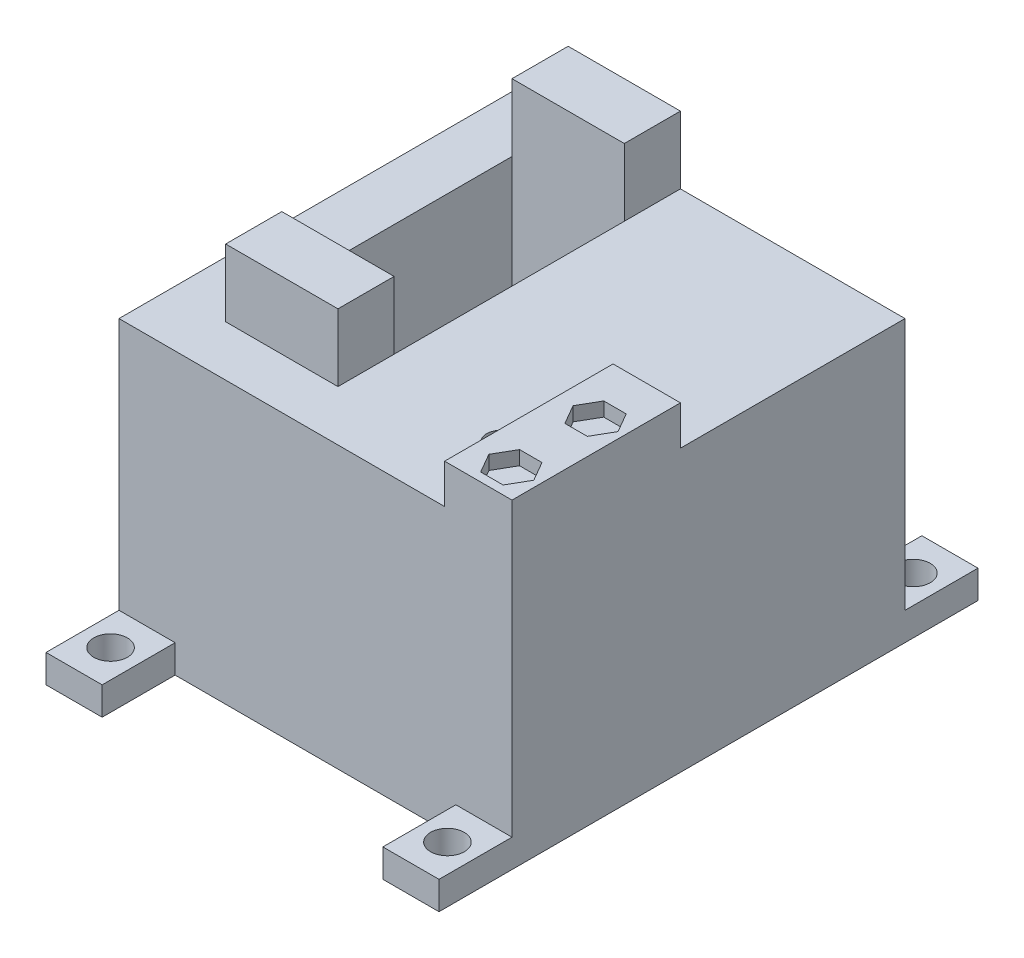
SolidWorks part; units mm, degrees
ref_plane "Front Plane" through (0, 0, 0) normal (0, 0, 1) x (1, 0, 0)
ref_plane "Top Plane" through (0, 0, 0) normal (0, 1, 0) x (1, 0, 0)
ref_plane "Right Plane" through (0, 0, 0) normal (1, 0, 0) x (0, 0, -1)
sketch "Sketch1" plane through (0, 0, 0) normal (0, 1, 0) x (1, 0, 0)
  line L1 (35, 35) -> (-35, 35)
  line L2 (35, 35) -> (35, -35)
  line L3 (35, -35) -> (-35, -35)
  line L4 (-35, 35) -> (-35, -35)
  line L5 (35, 35) -> (-35, -35) construction
  line L6 (35, -35) -> (-35, 35) construction
  point P0 (0, 0)
extrude "Boss-Extrude1" add sketch "Sketch1" along normal blind 50
sketch "Sketch2" plane through (0, 0, 0) normal (0, -1, 0) x (1, 0, 0)
  line L1 (0, 25) -> (-25, 25)
  line L2 (-25, 25) -> (-25, -25)
  line L3 (-25, -25) -> (25, -25)
  line L4 (0, 25) -> (25, 25)
  line L5 (25, 25) -> (25, -25)
extrude "Cut-Extrude1" cut sketch "Sketch2" against normal blind 40
sketch "Sketch3" plane through (0, 50, 0) normal (0, 1, 0) x (1, 0, 0)
  line L11 (-25, 25) -> (-5, 25)
  line L12 (-5, 25) -> (-5, -16)
  line L13 (-5, -16) -> (-25, -16)
  line L14 (-25, 25) -> (-25, -16)
extrude "Cut-Extrude2" cut sketch "Sketch3" against normal blind 40
sketch "Sketch4" plane through (0, 50, 0) normal (0, 1, 0) x (1, 0, 0)
  line L0 (-15, 25) -> (-15, 15)
  line L1 (-5, 25) -> (-25, 25) construction
  line L2 (-15, 15) -> (30, 15)
  line L4 (35, -35) -> (23, -35)
  line L6 (35, -35) -> (35, -5)
  line L8 (35, -5) -> (23, -5)
  line L9 (23, -35) -> (23, -5)
  line M24 (-35, -35) -> (35, -35)
  line M25 (35, -35) -> (35, 35)
extrude "Boss-Extrude2" add sketch "Sketch4" along normal blind 7 contours L9 L8 M24 M25
sketch "Sketch5" plane through (0, 57, 0) normal (0, 1, 0) x (1, 0, 0)
  line L3 (33.8817, -15) -> (31.8817, -18.4641)
  line L4 (31.8817, -18.4641) -> (27.8817, -18.4641)
  line L5 (27.8817, -18.4641) -> (25.8817, -15)
  line L6 (25.8817, -15) -> (27.8817, -11.5359)
  line L7 (27.8817, -11.5359) -> (31.8817, -11.5359)
  line L8 (31.8817, -11.5359) -> (33.8817, -15)
  line L9 (27.8817, -33.4641) -> (25.8817, -30)
  line L10 (25.8817, -30) -> (27.8817, -26.5359)
  line L11 (31.8817, -33.4641) -> (27.8817, -33.4641)
  line L12 (31.8817, -26.5359) -> (33.8817, -30)
  line L13 (33.8817, -30) -> (31.8817, -33.4641)
  line L14 (27.8817, -26.5359) -> (31.8817, -26.5359)
extrude "Cut-Extrude3" cut sketch "Sketch5" against normal blind 2.5
sketch "Sketch7" plane through (0, 50, 0) normal (0, 1, 0) x (1, 0, 0)
  line L0 (23, -35) -> (23, -20)
  line L1 (23, -35) -> (23, -5) construction
  circle A0 centre (18, -20) radius 2.5
extrude "Cut-Extrude4" cut sketch "Sketch7" against normal blind 52.5 contours A0
sketch "Sketch9" plane through (-35, 0, 0) normal (-1, 0, 0) x (0, 0, 1)
  line L3 (20, 10) -> (20, 0)
  line L4 (-35, 0) -> (35, 0) construction
  line L5 (20, 10) -> (10, 10)
  line L6 (10, 10) -> (10, 0)
extrude "Cut-Extrude5" cut sketch "Sketch9" against normal blind 52.5 and the other way through all
sketch "Sketch10" plane through (0, 0, 0) normal (0, -1, 0) x (1, 0, 0)
  line L1 (-25, -25) -> (25, -25) construction
  line L2 (-20, -25) -> (-20, -31)
  line L3 (-20, -31) -> (-10, -31)
  line L4 (-10, -31) -> (-10, -25)
  line L5 (-10, -25) -> (-20, -25)
extrude "Cut-Extrude6" cut sketch "Sketch10" against normal blind 35 contours L2 L3 L4 L5
sketch "Sketch11" plane through (0, 50, 0) normal (0, 1, 0) x (1, 0, 0)
  line L0 (-25, 25) -> (-25, 35)
  line L3 (-5, 25) -> (-5, 35)
  line L4 (-25, -16) -> (-25, -26)
  line L5 (-25, 35) -> (-5, 35)
  line L6 (-25, -26) -> (-5, -26)
  line L7 (-5, -26) -> (-5, -16)
  line L8 (-5, -16) -> (-25, -16)
  line M8 (-5, -16) -> (-25, -16)
  line M10 (-25, 25) -> (-5, 25)
  line M16 (35, 35) -> (-35, 35)
extrude "Boss-Extrude3" add sketch "Sketch11" along normal blind 12 contours L3 L0 M10 M16 | L6 L7 L4 M8
sketch "Sketch13" plane through (0, 0, 35) normal (0, 0, 1) x (1, 0, 0)
  line L0 (-35, 0) -> (-35, 5)
  line L1 (-35, 50) -> (-35, 0) construction
  line L2 (-35, 5) -> (-25, 5)
  line L3 (-25, 5) -> (-25, 0)
  line L4 (-35, 0) -> (35, 0) construction
  line L5 (35, 0) -> (35, 5)
  line L6 (35, 57) -> (35, 0) construction
  line L7 (35, 5) -> (25, 5)
  line L8 (-35, 0) -> (-25, 0)
  line L9 (35, 0) -> (25, 0)
  line L10 (25, 0) -> (25, 5)
extrude "Boss-Extrude4" add sketch "Sketch13" along normal blind 13
sketch "Sketch14" plane through (0, 0, -35) normal (0, 0, -1) x (-1, 0, 0)
  line L0 (-35, 0) -> (-35, 5)
  line L1 (-35, 0) -> (35, 0) construction
  line L2 (-35, 5) -> (-25, 5)
  line L3 (-25, 5) -> (-25, 0)
  line L4 (-25, 0) -> (-35, 0)
  line L5 (35, 0) -> (25, 0)
  line L6 (25, 0) -> (25, 5)
  line L7 (25, 5) -> (35, 5)
  line L8 (35, 50) -> (35, 0) construction
  line L9 (35, 5) -> (35, 0)
extrude "Boss-Extrude5" add sketch "Sketch14" along normal blind 13
sketch "Sketch15" plane through (0, 5, 0) normal (0, 1, 0) x (1, 0, 0)
  circle A0 centre (-29.8884, 41.355) radius 3
  circle A1 centre (-30, -41.5) radius 3
  circle A2 centre (30, -41.5) radius 3
  circle A3 centre (30, 41.5) radius 3
extrude "Cut-Extrude7" cut sketch "Sketch15" against normal blind 33
